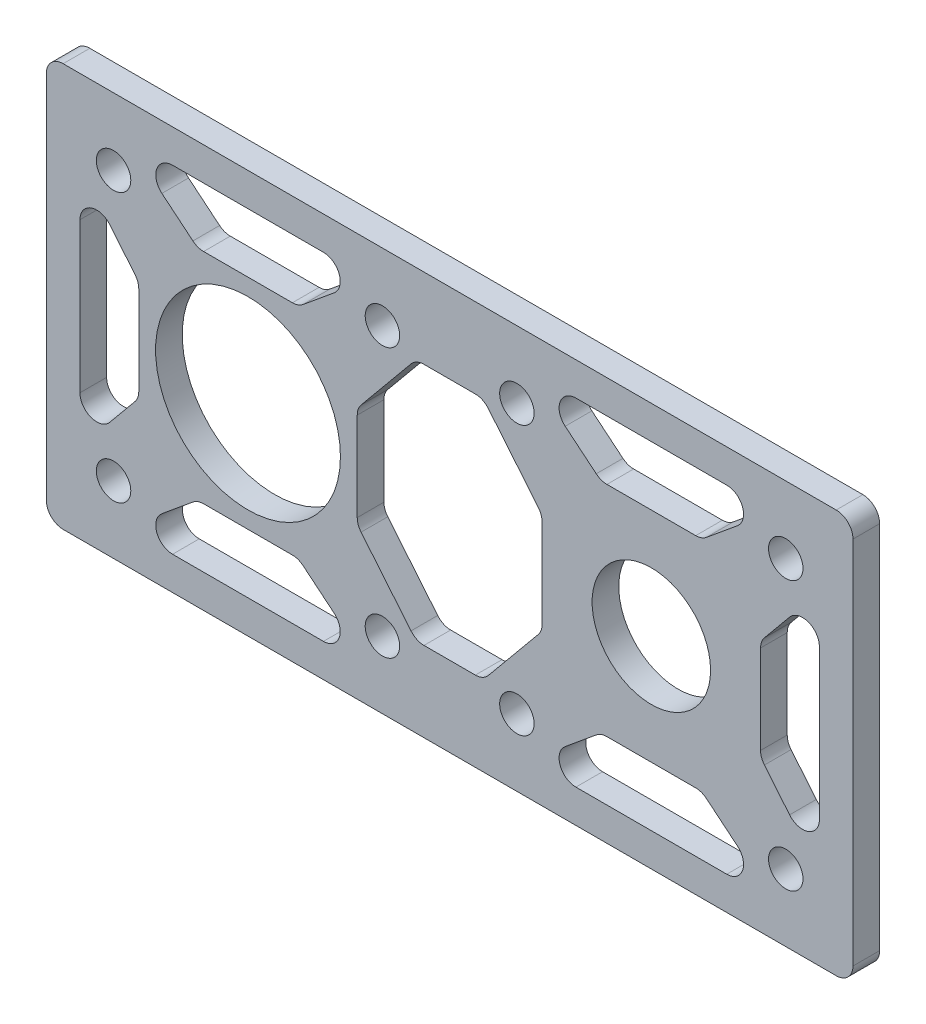
SolidWorks part; units mm, degrees
ref_plane "Front Plane" through (0, 0, 0) normal (0, 0, 1) x (1, 0, 0)
ref_plane "Top Plane" through (0, 0, 0) normal (0, 1, 0) x (1, 0, 0)
ref_plane "Right Plane" through (0, 0, 0) normal (1, 0, 0) x (0, 0, -1)
sketch "Sketch1" plane through (0, 0, 0) normal (0, 0, 1) x (1, 0, 0)
  line L0 (0, 0) -> (50000, 0) construction
  line L1 (48, -24) -> (-48, -24)
  line L2 (48, -24) -> (48, 24)
  line L3 (48, 24) -> (-48, 24)
  line L4 (-48, -24) -> (-48, 24)
  line L5 (48, -24) -> (-48, 24) construction
  line L6 (48, 24) -> (-48, -24) construction
  line L7 (0, 0) -> (0, -50000) construction
  line L8 (-38.5449, 20.05) -> (-30, 13)
  line L9 (-40, 16) -> (-8, 16) construction
  line L10 (-40, 16) -> (-40, -16) construction
  line L11 (-40, -16) -> (-8, -16) construction
  line L12 (-8, 16) -> (-8, -16) construction
  line L13 (-40, 16) -> (-8, -16) construction
  line L14 (-40, -16) -> (-8, 16) construction
  line L15 (-30, 13) -> (-18, 13)
  line L16 (-18, 13) -> (-9.4551, 20.05)
  line L17 (-9.4551, 20.05) -> (-38.5449, 20.05)
  line L18 (50, 26) -> (-50, 26) construction
  line L19 (-50, -26) -> (-50, 26) construction
  line L20 (50, -26) -> (-50, -26) construction
  line L21 (50, -26) -> (50, 26) construction
  line L22 (44, 20) -> (-44, 20) construction
  line L23 (-44, -20) -> (-44, 20) construction
  line L24 (44, -20) -> (-44, -20) construction
  line L25 (44, -20) -> (44, 20) construction
  line L26 (-18, -13) -> (-9.4551, -20.05)
  line L27 (-30, -13) -> (-18, -13)
  line L28 (-38.5449, -20.05) -> (-30, -13)
  line L29 (-9.4551, -20.05) -> (-38.5449, -20.05)
  line L30 (-44, 14.4843) -> (-44, -14.4843) construction
  line L31 (-44, -14.4843) -> (-37, -6) construction
  line L32 (-37, -6) -> (-37, 6) construction
  line L33 (-37, 6) -> (-44, 14.4843) construction
  line L34 (-24, 0) -> (-24, 50000) construction
  line L35 (-11, -6) -> (-11, 6)
  line L36 (-4, -14.4843) -> (-11, -6)
  line L38 (-11, 6) -> (-4, 14.4843)
  line L39 (4, -14.4843) -> (11, -6)
  line L41 (11, 6) -> (4, 14.4843)
  line L42 (11, -6) -> (11, 6)
  line L43 (30, -13) -> (18, -13)
  line L44 (38.5449, -20.05) -> (30, -13)
  line L45 (9.4551, -20.05) -> (38.5449, -20.05)
  line L46 (18, -13) -> (9.4551, -20.05)
  line L47 (37, -6) -> (37, 6)
  line L48 (44, -14.4843) -> (37, -6)
  line L49 (44, 14.4843) -> (44, -14.4843)
  line L50 (37, 6) -> (44, 14.4843)
  line L51 (18, 13) -> (9.4551, 20.05)
  line L52 (30, 13) -> (18, 13)
  line L53 (38.5449, 20.05) -> (30, 13)
  line L54 (9.4551, 20.05) -> (38.5449, 20.05)
  line L55 (-44, -14.4843) -> (-37, -6)
  line L56 (-44, 14.4843) -> (-44, -14.4843)
  line L57 (-37, 6) -> (-44, 14.4843)
  line L58 (-37, -6) -> (-37, 6)
  line L59 (-4, 14.4843) -> (4, 14.4843)
  line L60 (-4, -14.4843) -> (4, -14.4843)
  circle A0 centre (-40, 16) radius 2.05
  circle A1 centre (-8, 16) radius 2.05
  circle A2 centre (-8, -16) radius 2.05
  circle A3 centre (-40, -16) radius 2.05
  circle A4 centre (-24, 0) radius 11
  circle A5 centre (-8, -16) radius 4.05 construction
  circle A6 centre (-40, -16) radius 4.05 construction
  circle A7 centre (-24, 0) radius 13 construction
  circle A8 centre (-40, 16) radius 4.05 construction
  circle A9 centre (-8, 16) radius 4.05 construction
  circle A10 centre (-8, -16) radius 0.05 construction
  circle A11 centre (-40, -16) radius 0.05 construction
  circle A12 centre (-24, 0) radius 9 construction
  circle A13 centre (-40, 16) radius 0.05 construction
  circle A14 centre (-8, 16) radius 0.05 construction
  circle A15 centre (8, 16) radius 2.05
  circle A16 centre (8, -16) radius 2.05
  circle A17 centre (40, -16) radius 2.05
  circle A19 centre (40, 16) radius 2.05
  circle A20 centre (-36.7, 0) radius 2.05 construction
  circle A21 centre (11.3, 0) radius 2.05 construction
  circle A22 centre (24, 0) radius 7.05
  point P0 (0, 0)
  point P10 (-24, 0)
  dimension "D5" = 4.1
  dimension "D6" = 22
  dimension "D15" = 14.1
  dimension "D1" = 96
  dimension "D2" = 48
  dimension "D3" = 32
  dimension "D4" = 8
  dimension "D11" = 12
  dimension "D12" = 12
  dimension "D13" = 48
  dimension "D14" = 11.3
  dimension "D16" = 24
  dimension "D7" = 2
  dimension "D8" = 2
  dimension "D9" = 2
  dimension "D10" = 4
extrude "Boss-Extrude1" add sketch "Sketch1" along normal blind 3.175
fillet "Fillet1" radius 2 36 edges at (38.5449, -20.05, 1.5875) (9.4551, -20.05, 1.5875) (18, -13, 1.5875) (30, -13, 1.5875) (44, -14.4843, 1.5875) (37, -6, 1.5875) (37, 6, 1.5875) (44, 14.4843, 1.5875) (30, 13, 1.5875) (38.5449, 20.05, 1.5875) (9.4551, 20.05, 1.5875) (18, 13, 1.5875) (-48, -24, 1.5875) (-38.5449, -20.05, 1.5875) (-9.4551, -20.05, 1.5875) (-11, -6, 1.5875) (-30, -13, 1.5875) (-18, -13, 1.5875) (-11, 6, 1.5875) (-9.4551, 20.05, 1.5875) (-38.5449, 20.05, 1.5875) (-30, 13, 1.5875) (-18, 13, 1.5875) (-48, 24, 1.5875) (48, 24, 1.5875) (48, -24, 1.5875) (11, -6, 1.5875) (11, 6, 1.5875) (-44, -14.4843, 1.5875) (-37, -6, 1.5875) (-44, 14.4843, 1.5875) (-37, 6, 1.5875) (-4, -14.4843, 1.5875) (4, -14.4843, 1.5875) (4, 14.4843, 1.5875) (-4, 14.4843, 1.5875)
